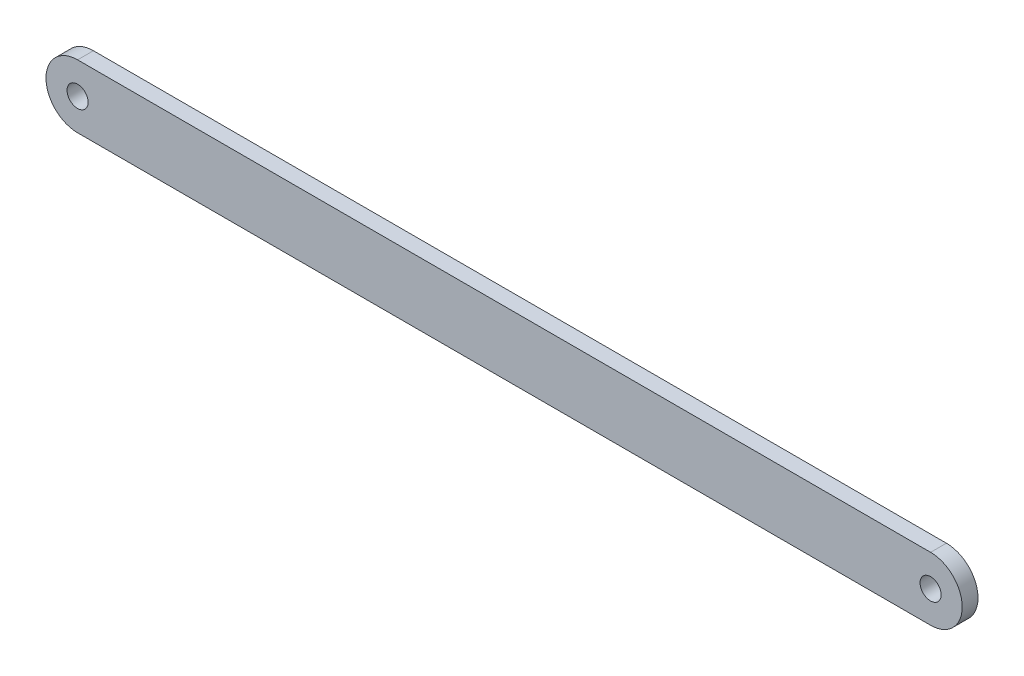
SolidWorks part; units mm, degrees
ref_plane "Front Plane" through (0, 0, 0) normal (0, 0, 1) x (1, 0, 0)
ref_plane "Top Plane" through (0, 0, 0) normal (0, 1, 0) x (1, 0, 0)
ref_plane "Right Plane" through (0, 0, 0) normal (1, 0, 0) x (0, 0, -1)
sketch "Sketch1" plane through (0, 0, 0) normal (0, 0, 1) x (1, 0, 0)
  line L0 (-35.3127, 0) -> (126.6389, 0) construction
  line L1 (-35.3127, 6) -> (126.6389, 6)
  line L2 (-35.3127, -6) -> (126.6389, -6)
  arc A0 (-35.3127, 6) -> (-35.3127, -6) centre (-35.3127, 0) ccw
  arc A1 (126.6389, -6) -> (126.6389, 6) centre (126.6389, 0) ccw
  circle A2 centre (-35.3127, 0) radius 2
  circle A3 centre (126.6389, 0) radius 2
  point P3 (45.6631, 0)
  dimension "D3" = 4
  dimension "D4" = 4
  dimension "D1" = 161.9516
  dimension "D2" = 12
extrude "Boss-Extrude3" add sketch "Sketch1" along normal blind 3
